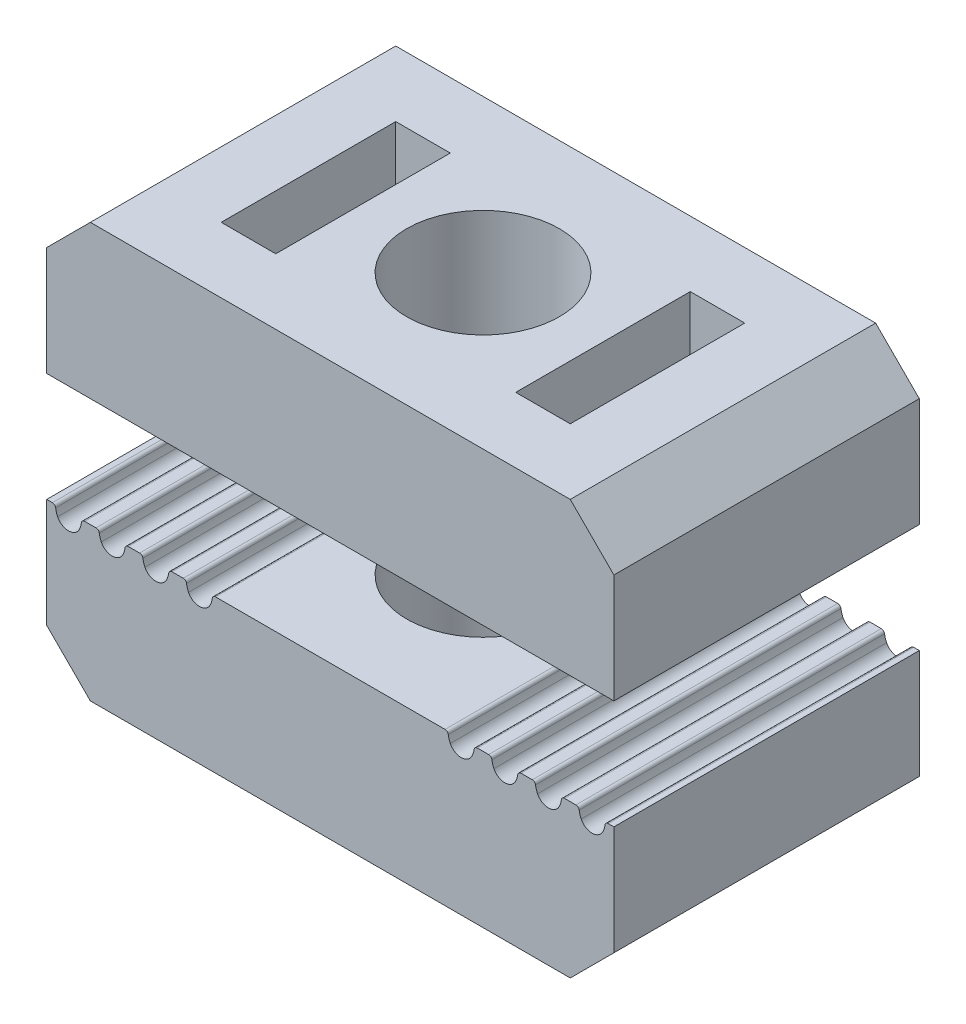
SolidWorks part; units mm, degrees
ref_plane "Alzado" through (0, 0, 0) normal (0, 0, 1) x (1, 0, 0)
ref_plane "Planta" through (0, 0, 0) normal (0, 1, 0) x (1, 0, 0)
ref_plane "Vista lateral" through (0, 0, 0) normal (1, 0, 0) x (0, 0, -1)
sketch "Croquis1" plane through (0, 0, 0) normal (0, 0, 1) x (1, 0, 0)
  line L0 (5, 7.63) -> (5, 7) construction
  line L1 (7.2598, 7) -> (6.7402, 7)
  line L2 (8.7402, 7) -> (9, 7)
  line L3 (9, 7) -> (9, 7.63) construction
  line L4 (9, 7.63) -> (5, 7.63) construction
  line L5 (8, 6.805) -> (8, 7.63) construction
  line L6 (5.2598, 7) -> (5, 7)
  line L7 (6, 3.0407) -> (6, 7.63) construction
  line L8 (9.2598, 7) -> (9, 7)
  line L9 (-11, 0) -> (11, 0)
  line L10 (11, 0) -> (13, 2)
  line L11 (-5, 0) -> (5, 0) construction
  line L12 (5, 7) -> (-5, 7)
  line L13 (11.2598, 7) -> (10.7402, 7)
  line L14 (12.7402, 7) -> (13, 7)
  line L15 (13, 2) -> (13, 7)
  line L16 (0, 7) -> (0, 0) construction
  line L17 (-6, 3.0407) -> (-6, 7.63) construction
  line L18 (-8, 6.805) -> (-8, 7.63) construction
  line L19 (-9, 7.63) -> (-5, 7.63) construction
  line L20 (-9, 7) -> (-9, 7.63) construction
  line L21 (-5, 7.63) -> (-5, 7) construction
  line L22 (-13, 2) -> (-13, 7)
  line L23 (-12.7402, 7) -> (-13, 7)
  line L24 (-11.2598, 7) -> (-10.7402, 7)
  line L25 (-11, 0) -> (-13, 2)
  line L26 (-9.2598, 7) -> (-9, 7)
  line L27 (-5.2598, 7) -> (-5, 7)
  line L28 (-8.7402, 7) -> (-9, 7)
  line L29 (-7.2598, 7) -> (-6.7402, 7)
  line L30 (-13, 9.5) -> (13, 9.5) construction
  line L31 (13, 17) -> (13, 12)
  line L32 (11, 19) -> (13, 17)
  line L33 (-11, 19) -> (11, 19)
  line L34 (-11, 19) -> (-13, 17)
  line L35 (-13, 17) -> (-13, 12)
  line L36 (-13, 12) -> (13, 12)
  arc A0 (7.2598, 7) -> (7.4085, 6.8696) centre (7.2598, 6.85) cw
  arc A1 (7.4085, 6.8696) -> (7.5011, 6.5618) centre (8.4, 7) ccw
  arc A2 (7.5011, 6.5618) -> (8.4989, 6.5618) centre (8, 6.805) ccw
  arc A3 (8.4989, 6.5618) -> (8.5915, 6.8696) centre (7.6, 7) ccw
  arc A4 (8.5915, 6.8696) -> (8.7402, 7) centre (8.7402, 6.85) cw
  arc A5 (6.7402, 7) -> (6.5915, 6.8696) centre (6.7402, 6.85) ccw
  arc A6 (6.5915, 6.8696) -> (6.4989, 6.5618) centre (5.6, 7) cw
  arc A7 (5.2598, 7) -> (5.4085, 6.8696) centre (5.2598, 6.85) cw
  arc A8 (5.4085, 6.8696) -> (5.5011, 6.5618) centre (6.4, 7) ccw
  arc A9 (5.5011, 6.5618) -> (6.4989, 6.5618) centre (6, 6.805) ccw
  arc A10 (9.2598, 7) -> (9.4085, 6.8696) centre (9.2598, 6.85) cw
  arc A11 (9.4085, 6.8696) -> (9.5011, 6.5618) centre (10.4, 7) ccw
  arc A12 (9.5011, 6.5618) -> (10.4989, 6.5618) centre (10, 6.805) ccw
  arc A13 (10.5915, 6.8696) -> (10.4989, 6.5618) centre (9.6, 7) cw
  arc A14 (10.7402, 7) -> (10.5915, 6.8696) centre (10.7402, 6.85) ccw
  arc A15 (11.2598, 7) -> (11.4085, 6.8696) centre (11.2598, 6.85) cw
  arc A16 (11.4085, 6.8696) -> (11.5011, 6.5618) centre (12.4, 7) ccw
  arc A17 (11.5011, 6.5618) -> (12.4989, 6.5618) centre (12, 6.805) ccw
  arc A18 (12.4989, 6.5618) -> (12.5915, 6.8696) centre (11.6, 7) ccw
  arc A19 (12.5915, 6.8696) -> (12.7402, 7) centre (12.7402, 6.85) cw
  arc A20 (-12.5915, 6.8696) -> (-12.7402, 7) centre (-12.7402, 6.85) ccw
  arc A21 (-12.4989, 6.5618) -> (-12.5915, 6.8696) centre (-11.6, 7) cw
  arc A22 (-11.5011, 6.5618) -> (-12.4989, 6.5618) centre (-12, 6.805) cw
  arc A23 (-11.4085, 6.8696) -> (-11.5011, 6.5618) centre (-12.4, 7) cw
  arc A24 (-11.2598, 7) -> (-11.4085, 6.8696) centre (-11.2598, 6.85) ccw
  arc A25 (-10.7402, 7) -> (-10.5915, 6.8696) centre (-10.7402, 6.85) cw
  arc A26 (-10.5915, 6.8696) -> (-10.4989, 6.5618) centre (-9.6, 7) ccw
  arc A27 (-9.5011, 6.5618) -> (-10.4989, 6.5618) centre (-10, 6.805) cw
  arc A28 (-9.4085, 6.8696) -> (-9.5011, 6.5618) centre (-10.4, 7) cw
  arc A29 (-9.2598, 7) -> (-9.4085, 6.8696) centre (-9.2598, 6.85) ccw
  arc A30 (-5.5011, 6.5618) -> (-6.4989, 6.5618) centre (-6, 6.805) cw
  arc A31 (-5.4085, 6.8696) -> (-5.5011, 6.5618) centre (-6.4, 7) cw
  arc A32 (-5.2598, 7) -> (-5.4085, 6.8696) centre (-5.2598, 6.85) ccw
  arc A33 (-6.5915, 6.8696) -> (-6.4989, 6.5618) centre (-5.6, 7) ccw
  arc A34 (-6.7402, 7) -> (-6.5915, 6.8696) centre (-6.7402, 6.85) cw
  arc A35 (-8.5915, 6.8696) -> (-8.7402, 7) centre (-8.7402, 6.85) ccw
  arc A36 (-8.4989, 6.5618) -> (-8.5915, 6.8696) centre (-7.6, 7) cw
  arc A37 (-7.5011, 6.5618) -> (-8.4989, 6.5618) centre (-8, 6.805) cw
  arc A38 (-7.4085, 6.8696) -> (-7.5011, 6.5618) centre (-8.4, 7) cw
  arc A39 (-7.2598, 7) -> (-7.4085, 6.8696) centre (-7.2598, 6.85) ccw
  dimension "D2" = 0.15
  dimension "D3" = 1
  dimension "D1" = 0.555
  dimension "D5" = 0.4
  dimension "D4" = 0.4
  dimension "D6" = 0.75
  dimension "D7" = 1.38
  dimension "D8" = 2
  dimension "D9" = 0.4
  dimension "D10" = 0.4
  dimension "D11" = 1
  dimension "D12" = 1
  dimension "D13" = 5
  dimension "D14" = 45
  dimension "D15" = 2
  dimension "D16" = 8
  dimension "D17" = 5
  dimension "D18" = 7
  dimension "D19" = 2.5
extrude "Saliente-Extruir1" add sketch "Croquis1" along normal blind 14
sketch "Croquis2" plane through (0, 19, 0) normal (0, 1, 0) x (1, 0, 0)
  line L0 (0, 0) -> (0, -14) construction
  line L1 (11, -14) -> (-11, -14) construction
  circle A0 centre (0, -7) radius 3.5
  dimension "D1" = 7
extrude "Cortar-Extruir1" cut sketch "Croquis2" against normal through all
sketch "Croquis3" plane through (0, 19, 0) normal (0, 1, 0) x (1, 0, 0)
  line L0 (11, -14) -> (-11, -14) construction
  line L1 (-8, -3) -> (-5.5, -3)
  line L2 (-8, -3) -> (-8, -11)
  line L3 (-8, -11) -> (-5.5, -11)
  line L4 (-5.5, -3) -> (-5.5, -11)
  line L5 (5.5, -3) -> (8, -3)
  line L6 (5.5, -3) -> (5.5, -11)
  line L7 (5.5, -11) -> (8, -11)
  line L8 (8, -3) -> (8, -11)
  circle A1 centre (0, -7) radius 3.5 construction
  dimension "D1" = 8
  dimension "D2" = 2.5
  dimension "D3" = 2
  dimension "D4" = 2
  dimension "D5" = 3
extrude "Cortar-Extruir2" cut sketch "Croquis3" against normal up to next (7 mm away)
fillet "Redondeo1" radius 1 2 edges at (8, 12, 7) (-8, 12, 7)
